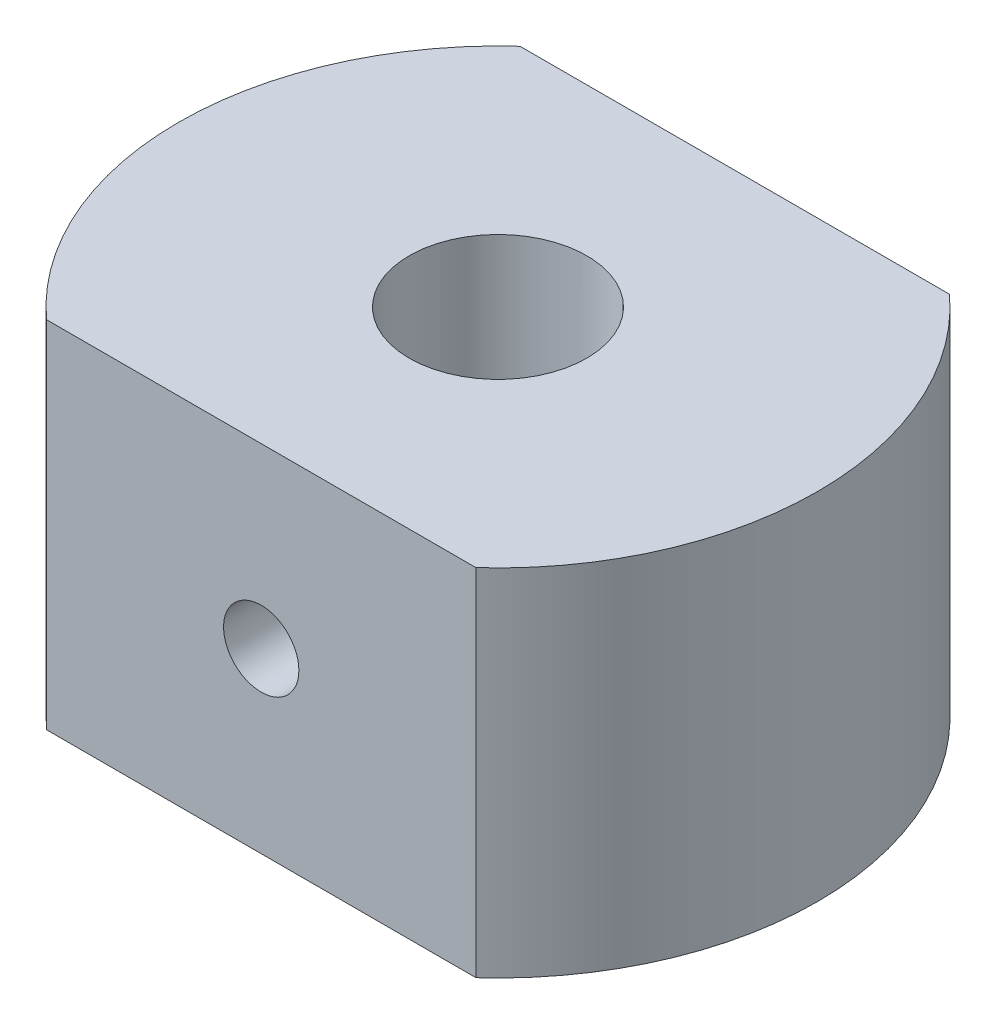
SolidWorks part; units mm, degrees
material "Brass"
ref_plane "Front Plane" through (0, 0, 0) normal (0, 0, 1) x (1, 0, 0)
ref_plane "Top Plane" through (0, 0, 0) normal (0, 1, 0) x (1, 0, 0)
ref_plane "Right Plane" through (0, 0, 0) normal (1, 0, 0) x (0, 0, -1)
other "Center of Mass"
sketch "Sketch1" plane through (0, 0, 0) normal (0, 1, 0) x (1, 0, 0)
  circle A0 centre (0, 0) radius 17.145
  dimension "D1" = 34.29
extrude "Boss-Extrude1" add sketch "Sketch1" along normal blind 19.05
sketch "Sketch2" plane through (0, 19.05, 0) normal (0, 1, 0) x (1, 0, 0)
  circle A0 centre (0, 0) radius 4.7625
  dimension "D1" = 9.525
extrude "Cut-Extrude1" cut sketch "Sketch2" against normal through all
sketch "Sketch3" plane through (0, 0, 0) normal (0, 0, 1) x (1, 0, 0)
  line L0 (0, 0) -> (0, 19.05) construction
  line L1 (4.7625, 19.05) -> (-4.7625, 19.05) construction
  circle A0 centre (0, 9.525) radius 2.0193
  point P7 (0, 9.525)
  dimension "D1" = 4.0386
extrude "10-32 Tapped Hole" cut sketch "Sketch3" against normal mid plane 101.6
sketch "Sketch4" plane through (0, 19.05, 0) normal (0, 1, 0) x (1, 0, 0)
  line L1 (-17.145, -12.7) -> (17.145, -12.7)
  line L2 (-17.145, -12.7) -> (-17.145, 12.7)
  line L3 (-17.145, 12.7) -> (17.145, 12.7)
  line L4 (17.145, -12.7) -> (17.145, 12.7)
  line L5 (-17.145, -12.7) -> (17.145, 12.7) construction
  line L6 (-17.145, 12.7) -> (17.145, -12.7) construction
  circle A0 centre (0, 0) radius 17.145 construction
  point P0 (0, 0)
  dimension "D1" = 25.4
extrude "Fit in Slot" cut sketch "Sketch4" against normal through all flip side to cut
